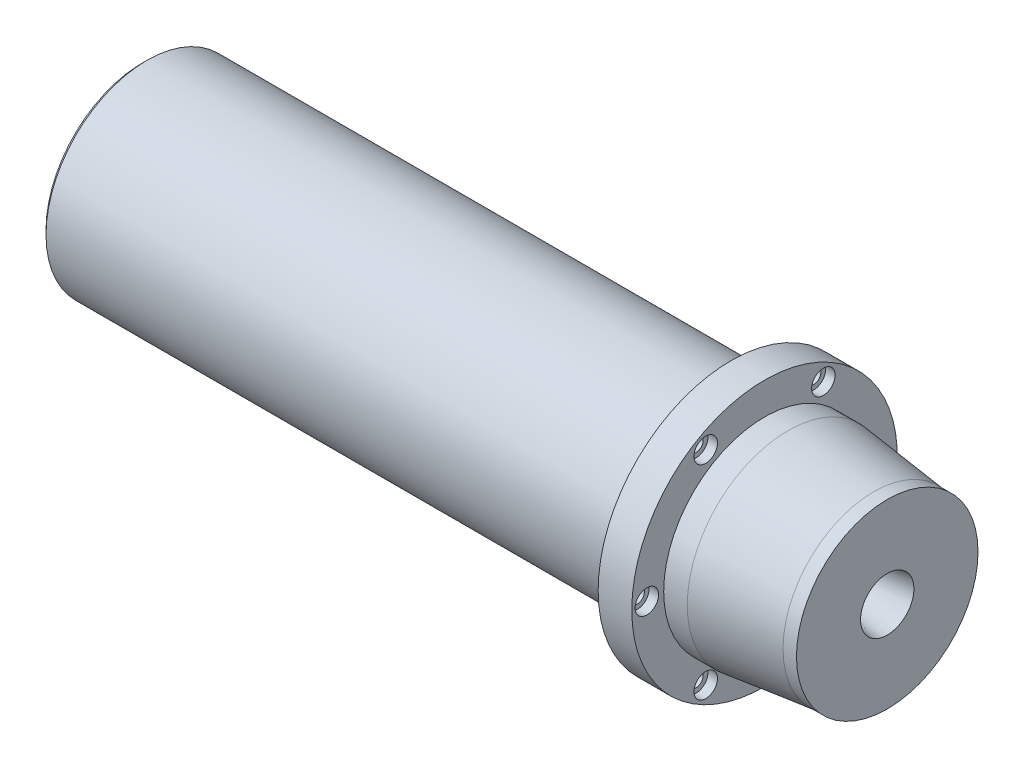
SolidWorks part; units mm, degrees
ref_plane "Front Plane" through (0, 0, 0) normal (0, 0, 1) x (1, 0, 0)
ref_plane "Top Plane" through (0, 0, 0) normal (0, 1, 0) x (1, 0, 0)
ref_plane "Right Plane" through (0, 0, 0) normal (1, 0, 0) x (0, 0, -1)
sketch "Sketch1" plane through (0, 0, 0) normal (0, 1, 0) x (1, 0, 0)
  line L0 (0, 0) -> (500, 0) construction
  line L1 (0, 0) -> (0, 60)
  line L2 (0, 60) -> (350, 60)
  line L3 (350, 60) -> (350, 79)
  line L4 (350, 79) -> (370, 79)
  line L5 (370, 79) -> (370, 60)
  line L6 (370, 60) -> (384, 60)
  line L9 (382.6, 0) -> (0, 0)
  line L10 (443, 54) -> (435, 54)
  line L11 (435, 54) -> (384, 60)
  line L13 (443, 15.875) -> (443, 54)
  line L17 (382.6, 8.8165) -> (382.6, 0)
  line L18 (394.6, 8.8165) -> (443, 15.875)
  line L19 (394.6, 8.8165) -> (382.6, 8.8165)
  point P10 (360, 79)
  dimension "D1" = 500
  dimension "D2" = 60
  dimension "D3" = 350
  dimension "D4" = 79
  dimension "D5" = 20
  dimension "D6" = 60
  dimension "D7" = 14
  dimension "D8" = 8
  dimension "D9" = 15.875
  dimension "D10" = 48.4
  dimension "D11" = 0
  dimension "D12" = 73
  dimension "D14" = 54
  dimension "D15" = 12
  dimension "D16" = 8.8165
revolve "Revolve1" add sketch "Sketch1" angle 360 about L0
chamfer "Chamfer1" distance 2.5 angle 45 1 edges at (0, 0, 60)
sketch "Sketch5" plane through (370, 0, 0) normal (1, 0, 0) x (0, 0, -1)
  line L0 (86.9, 0) -> (-86.9, 0) construction
  circle A0 centre (0, 0) radius 60 construction
  point P0 (-70, 0)
  point P7 (-35, 60.6218)
  point P8 (35, 60.6218)
  point P9 (70, 0)
  point P10 (35, -60.6218)
  point P11 (-35, -60.6218)
  point P12 (0, 0)
  dimension "D1" = 70
  dimension "D2" = 6
hole_wizard "CBORE for M8 Hex Head Bolt2" positions "Sketch5" profile "Sketch6" counterbore size "M8" standard "ANSI Metric"
sketch "Sketch6" plane through (370, 0, 70) normal (0, 1, 0) x (0, 0, -1)
  line L0 (0, 0) -> (0, 370)
  line L1 (0, 370) -> (4.2, 370)
  line L3 (4.2, 370) -> (4.2, 5.68)
  line L4 (4.2, 5.68) -> (7, 5.68)
  line L5 (7, 5.68) -> (7, 0)
  line L7 (7, 0) -> (0, 0)
  line L11 (0, -6.35) -> (0, 107.95) construction
  dimension "Thru Hole Dia." = 8.4
  dimension "Thru Hole Depth" = 370
  dimension "C'Bore Dia." = 14
  dimension "C'Bore Depth" = 5.68
